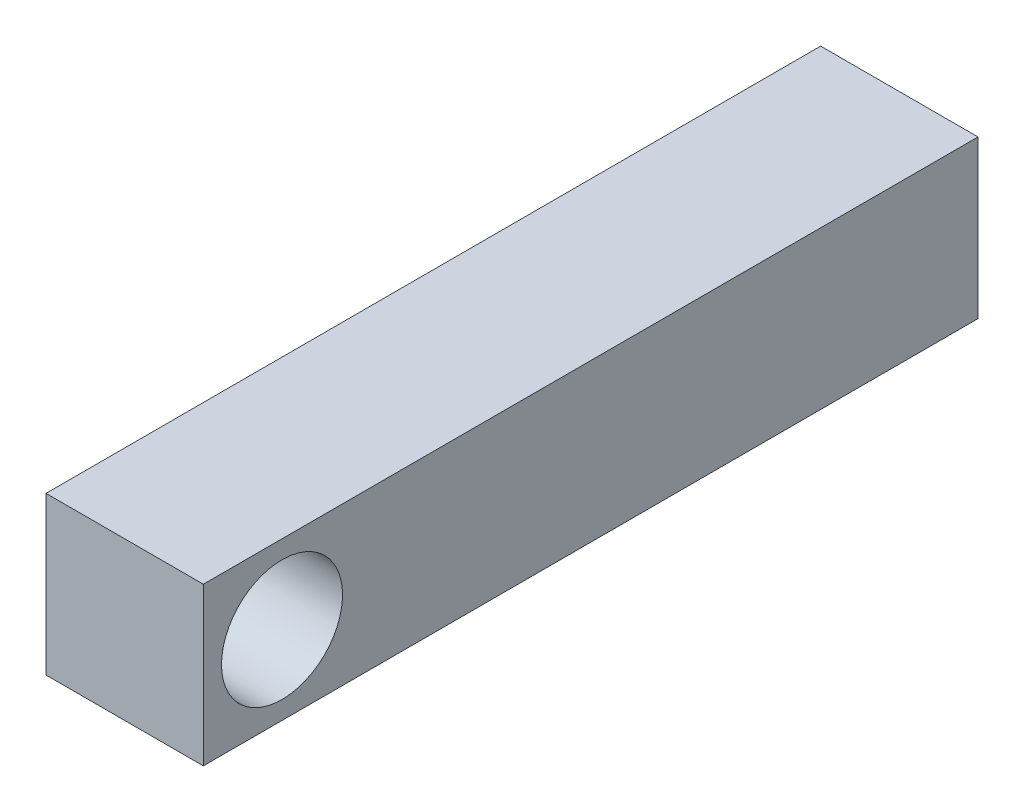
SolidWorks part; units mm, degrees
material "Plain Carbon Steel"
ref_plane "Front Plane" through (0, 0, 0) normal (0, 0, 1) x (1, 0, 0)
ref_plane "Top Plane" through (0, 0, 0) normal (0, 1, 0) x (1, 0, 0)
ref_plane "Right Plane" through (0, 0, 0) normal (1, 0, 0) x (0, 0, -1)
sketch "Sketch1" plane through (0, 0, 0) normal (0, 0, 1) x (1, 0, 0)
  line L1 (20.6375, -20.6375) -> (-20.6375, -20.6375)
  line L2 (20.6375, -20.6375) -> (20.6375, 20.6375)
  line L3 (20.6375, 20.6375) -> (-20.6375, 20.6375)
  line L4 (-20.6375, -20.6375) -> (-20.6375, 20.6375)
  line L5 (20.6375, -20.6375) -> (-20.6375, 20.6375) construction
  line L6 (20.6375, 20.6375) -> (-20.6375, -20.6375) construction
  point P0 (0, 0)
  dimension "D1" = 41.275
extrude "Boss-Extrude1" add sketch "Sketch1" along normal blind 203.2
sketch "Sketch3" plane through (0, -20.6375, 0) normal (0, -1, 0) x (1, 0, 0)
  line L0 (0, 0) -> (0, 20.6375) construction
  line L1 (0, 20.6375) -> (20.6375, 20.6375) construction
  line L2 (20.6375, 203.2) -> (20.6375, 0) construction
  line L3 (0, 20.6375) -> (-20.6375, 20.6375) construction
  line L4 (-20.6375, 203.2) -> (-20.6375, 0) construction
  circle A0 centre (0, 20.6375) radius 15.875
  dimension "D1" = 31.75
extrude "Cut-Extrude2" cut sketch "Sketch3" against normal blind 31.75
sketch "Sketch4" plane through (-20.6375, 0, 0) normal (-1, 0, 0) x (0, 0, 1)
  line L0 (182.5625, 0) -> (203.2, 0) construction
  line L1 (203.2, 20.6375) -> (203.2, -20.6375) construction
  line L2 (182.5625, 0) -> (182.5625, 20.6375) construction
  line L3 (203.2, 20.6375) -> (0, 20.6375) construction
  line L4 (182.5625, 0) -> (182.5625, -20.6375) construction
  line L5 (203.2, -20.6375) -> (0, -20.6375) construction
  circle A0 centre (182.5625, 0) radius 15.875
  dimension "D1" = 31.75
extrude "Cut-Extrude3" cut sketch "Sketch4" against normal through all
